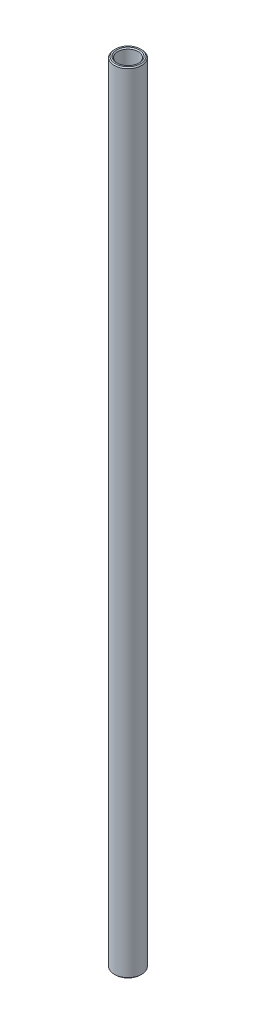
SolidWorks part; units mm, degrees
material "AISI 304"
ref_plane "Спереди" through (0, 0, 0) normal (0, 0, 1) x (1, 0, 0)
ref_plane "Сверху" through (0, 0, 0) normal (0, 1, 0) x (1, 0, 0)
ref_plane "Справа" through (0, 0, 0) normal (1, 0, 0) x (0, 0, -1)
other "Configuration Table"
sketch "Эскиз1" plane through (0, 0, 0) normal (0, 1, 0) x (1, 0, 0)
  circle A0 centre (0, 0) radius 4
  circle A1 centre (0, 0) radius 3
  dimension "D1" = 8
  dimension "D2" = 6
extrude "Бобышка-Вытянуть1" add sketch "Эскиз1" along normal blind 230
chamfer "Фаска1" distance 0.3 angle 45 4 edges at (0, 230, 3) (0, 0, 3) (0, 0, 4) (0, 230, 4)
